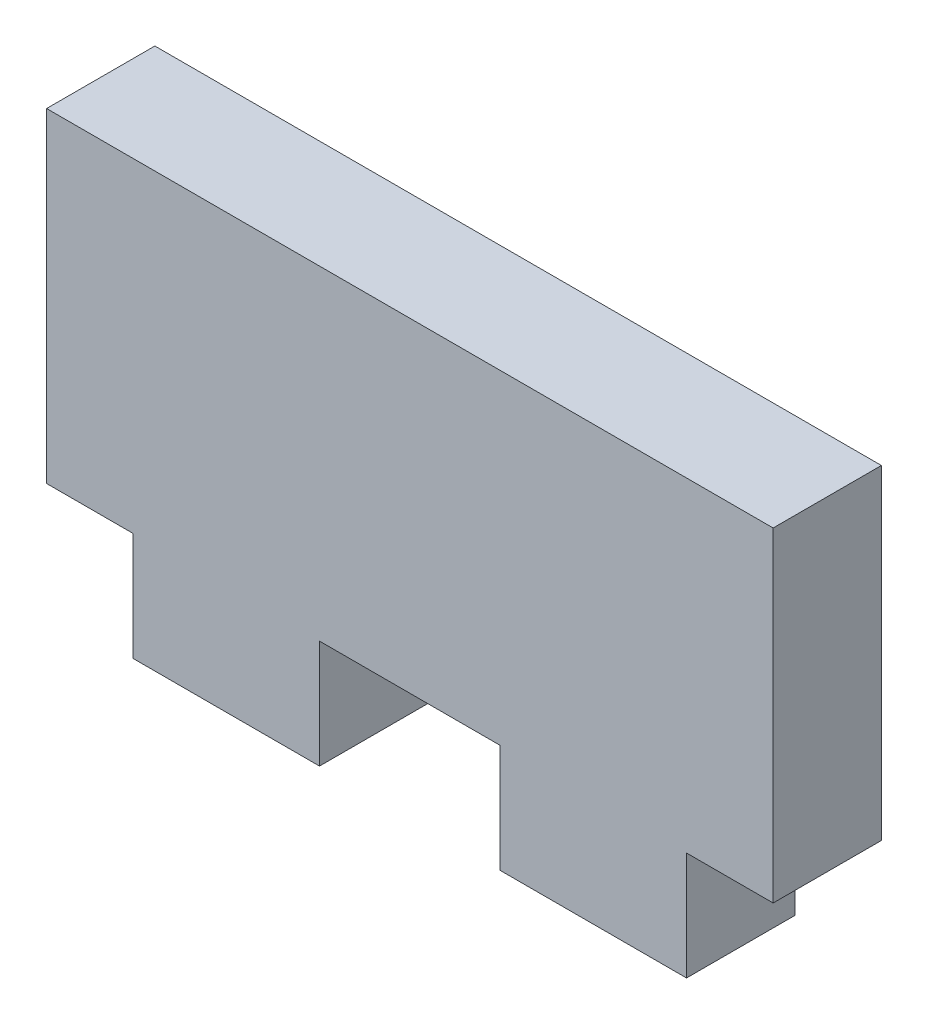
SolidWorks part; units mm, degrees
ref_plane "Front" through (0, 0, 0) normal (0, 0, 1) x (1, 0, 0)
ref_plane "Top" through (0, 0, 0) normal (0, 1, 0) x (1, 0, 0)
ref_plane "Right" through (0, 0, 0) normal (1, 0, 0) x (0, 0, -1)
sketch "Sketch1" plane through (0, 0, 0) normal (0, 0, 1) x (1, 0, 0)
  line L0 (-44.3915, 39.6141) -> (-10.8363, 39.6141)
  line L1 (-14.8363, 19.6141) -> (-23.4405, 19.6141)
  line L2 (-31.7872, 19.6141) -> (-40.3915, 19.6141)
  line L3 (-31.7872, 19.6141) -> (-31.7872, 24.6141)
  line L4 (-23.4405, 19.6141) -> (-23.4405, 24.6141)
  line L5 (-23.4405, 24.6141) -> (-31.7872, 24.6141)
  line L6 (-14.8363, 19.6141) -> (-14.8363, 24.6141)
  line L10 (-14.8363, 24.6141) -> (-10.8363, 24.6141)
  line L11 (-40.3915, 19.6141) -> (-40.3915, 24.6141)
  line L12 (-40.3915, 24.6141) -> (-44.3915, 24.6141)
  line L13 (-10.8363, 24.6141) -> (-10.8363, 39.6141)
  line L14 (-44.3915, 24.6141) -> (-44.3915, 39.6141)
extrude "Boss-Extrude1" add sketch "Sketch1" along normal blind 5
